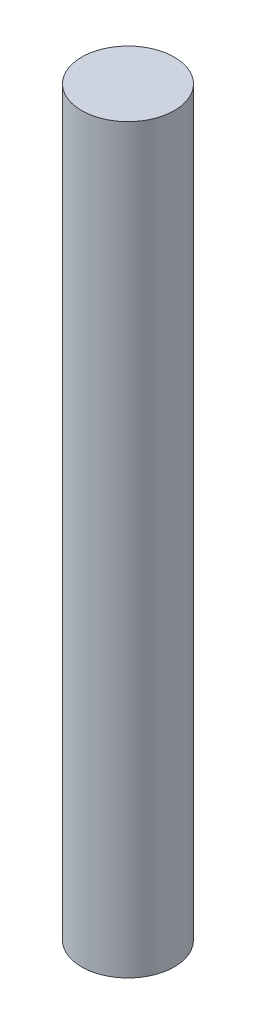
SolidWorks part; units mm, degrees
material "PP Kopolimer"
ref_plane "Front Plane" through (0, 0, 0) normal (0, 0, 1) x (1, 0, 0)
ref_plane "Top Plane" through (0, 0, 0) normal (0, 1, 0) x (1, 0, 0)
ref_plane "Right Plane" through (0, 0, 0) normal (1, 0, 0) x (0, 0, -1)
sketch "Szkic1" plane through (0, 0, 0) normal (0, 1, 0) x (1, 0, 0)
  circle A0 centre (0, 0) radius 0.125
extrude "Dodanie-wyciągnięcie1" add sketch "Szkic1" along normal blind 2
